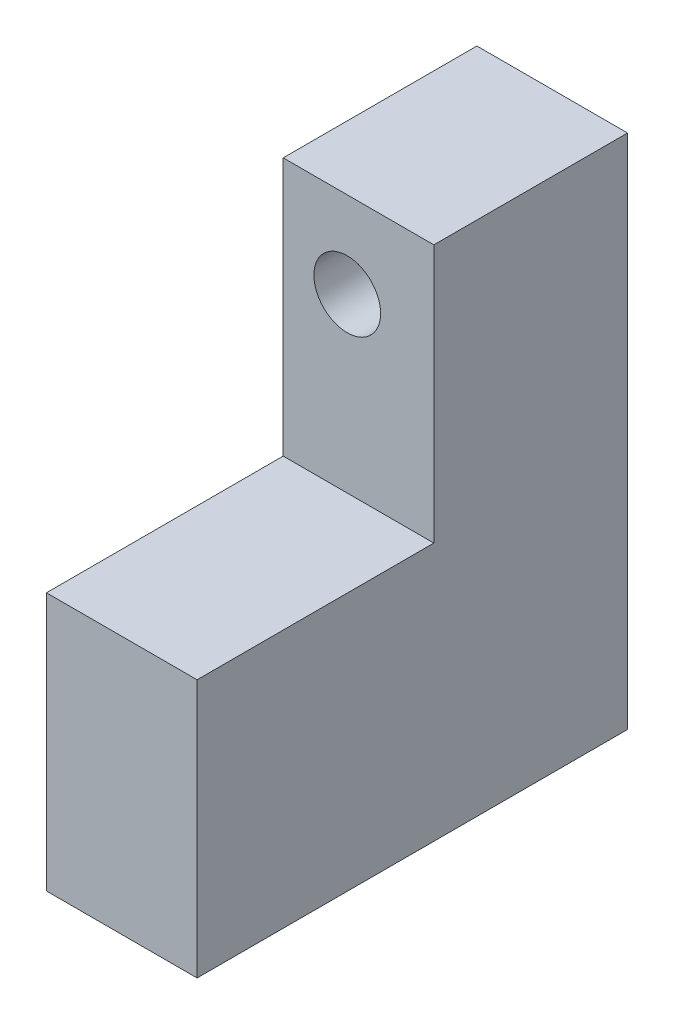
SolidWorks part; units mm, degrees
ref_plane "前视基准面" through (0, 0, 0) normal (0, 0, 1) x (1, 0, 0)
ref_plane "上视基准面" through (0, 0, 0) normal (0, 1, 0) x (1, 0, 0)
ref_plane "右视基准面" through (0, 0, 0) normal (1, 0, 0) x (0, 0, -1)
other "Configuration Table"
sketch "草图1" plane through (0, 0, 0) normal (0, 0, 1) x (1, 0, 0)
  line L0 (5, 0) -> (108, 0) construction
  line L1 (0, 62) -> (0, 5) construction
  line L2 (7.0251, 28.5) -> (0.0251, 28.5)
  line L3 (7.0251, 28.5) -> (7.0251, 4.5)
  line L4 (7.0251, 4.5) -> (0.0251, 4.5)
  line L5 (0.0251, 28.5) -> (0.0251, 4.5)
  circle A0 centre (3, 24.5) radius 1.55
  arc A1 (0, 5) -> (5, 0) centre (5, 5) ccw construction
  dimension "D4" = 3.1
  dimension "D1" = 24
  dimension "D2" = 7
  dimension "D3" = 3
  dimension "D5" = 4.5
extrude "凸台-拉伸1" add sketch "草图1" along normal blind 9
sketch "草图2" plane through (0, 0, 9) normal (0, 0, 1) x (1, 0, 0)
  line L0 (0.0251, 16.5) -> (7.0251, 16.5) construction
  line L1 (0.0251, 28.5) -> (0.0251, 4.5) construction
  line L2 (7.0251, 4.5) -> (7.0251, 28.5) construction
  line L4 (0.0251, 16.5) -> (7.0251, 16.5)
  line L5 (0.0251, 16.5) -> (0.0251, 4.5)
  line L6 (0.0251, 4.5) -> (7.0251, 4.5)
  line L7 (7.0251, 16.5) -> (7.0251, 4.5)
extrude "凸台-拉伸2" add sketch "草图2" along normal blind 11 contours L5 L4 L7 L6
sketch "草图3" plane through (0, 4.5, 0) normal (0, -1, 0) x (-1, 0, 0)
  line L0 (-0.0251, -20) -> (-7.0251, -20) construction
  line L1 (-3.5251, -20) -> (-3.5251, 0) construction
  line L2 (-0.0251, 0) -> (-7.0251, 0) construction
  circle A0 centre (-3.5251, -5) radius 1.55
  circle A1 centre (-3.5251, -15) radius 1.55
  point P10 (0, 0)
  point P11 (0, 0)
  dimension "D1" = 3.1
  dimension "D2" = 3.1
  dimension "D3" = 5
  dimension "D4" = 5
extrude "切除-拉伸1" cut sketch "草图3" against normal blind 5
